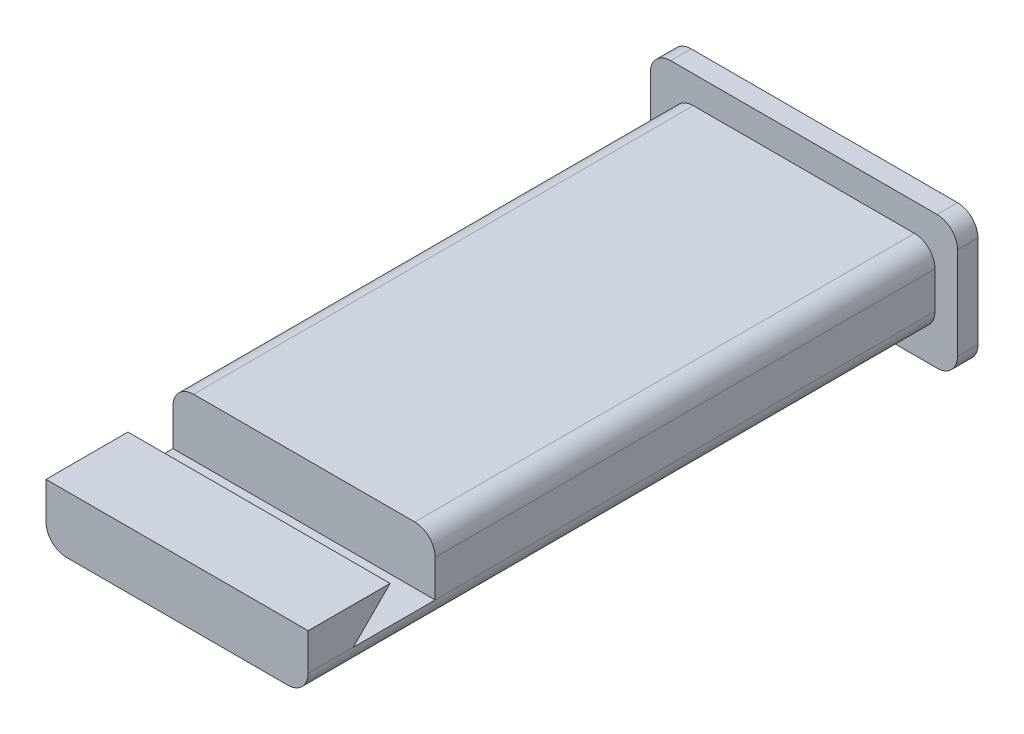
SolidWorks part; units mm, degrees
ref_plane "Front Plane" through (0, 0, 0) normal (0, 0, 1) x (1, 0, 0)
ref_plane "Top Plane" through (0, 0, 0) normal (0, 1, 0) x (1, 0, 0)
ref_plane "Right Plane" through (0, 0, 0) normal (1, 0, 0) x (0, 0, -1)
sketch "Sketch1" plane through (0, 0, 0) normal (0, 0, 1) x (1, 0, 0)
  line L1 (-12.8, -3.8) -> (12.8, -3.8)
  line L2 (-12.8, -3.8) -> (-12.8, 3.8)
  line L3 (-12.8, 3.8) -> (12.8, 3.8)
  line L4 (12.8, -3.8) -> (12.8, 3.8)
  line L5 (-12.8, -3.8) -> (12.8, 3.8) construction
  line L6 (-12.8, 3.8) -> (12.8, -3.8) construction
  point P0 (0, 0)
  dimension "D1" = 25.6
  dimension "D2" = 7.6
extrude "Boss-Extrude1" add sketch "Sketch1" along normal blind 61.2
fillet "Fillet1" radius 2 4 edges at (-12.8, -3.8, 30.6) (12.8, -3.8, 30.6) (12.8, 3.8, 30.6) (-12.8, 3.8, 30.6)
sketch "Sketch2" plane through (0, 0, 0) normal (0, 0, -1) x (-1, 0, 0)
  line L1 (-15, -6.5) -> (15, -6.5)
  line L2 (-15, -6.5) -> (-15, 6.5)
  line L3 (-15, 6.5) -> (15, 6.5)
  line L4 (15, -6.5) -> (15, 6.5)
  line L5 (-15, -6.5) -> (15, 6.5) construction
  line L6 (-15, 6.5) -> (15, -6.5) construction
  point P0 (0, 0)
  dimension "D1" = 13
  dimension "D2" = 30
extrude "Boss-Extrude2" add sketch "Sketch2" along normal blind 2
fillet "Fillet2" radius 2 4 edges at (-15, -6.5, -1) (15, -6.5, -1) (15, 6.5, -1) (-15, 6.5, -1)
sketch "Sketch3" plane through (-12.8, 0, 0) normal (-1, 0, 0) x (0, 0, 1)
  line L0 (48.8, -1.8) -> (56.8, -1.8)
  line L1 (0, -1.8) -> (61.2, -1.8) construction
  line L2 (56.8, -1.8) -> (53.2, 1.8)
  line L3 (61.2, 1.8) -> (0, 1.8) construction
  line L4 (53.2, 1.8) -> (61.2, 1.8)
  line L5 (61.2, 1.8) -> (61.2, 3.8)
  line L6 (61.2, 3.8) -> (48.8, 3.8)
  line L7 (0, 3.8) -> (61.2, 3.8) construction
  line L8 (48.8, 3.8) -> (48.8, -1.8)
  dimension "D1" = 8
  dimension "D2" = 8
  dimension "D3" = 45
extrude "Cut-Extrude1" cut sketch "Sketch3" against normal blind 25.6
